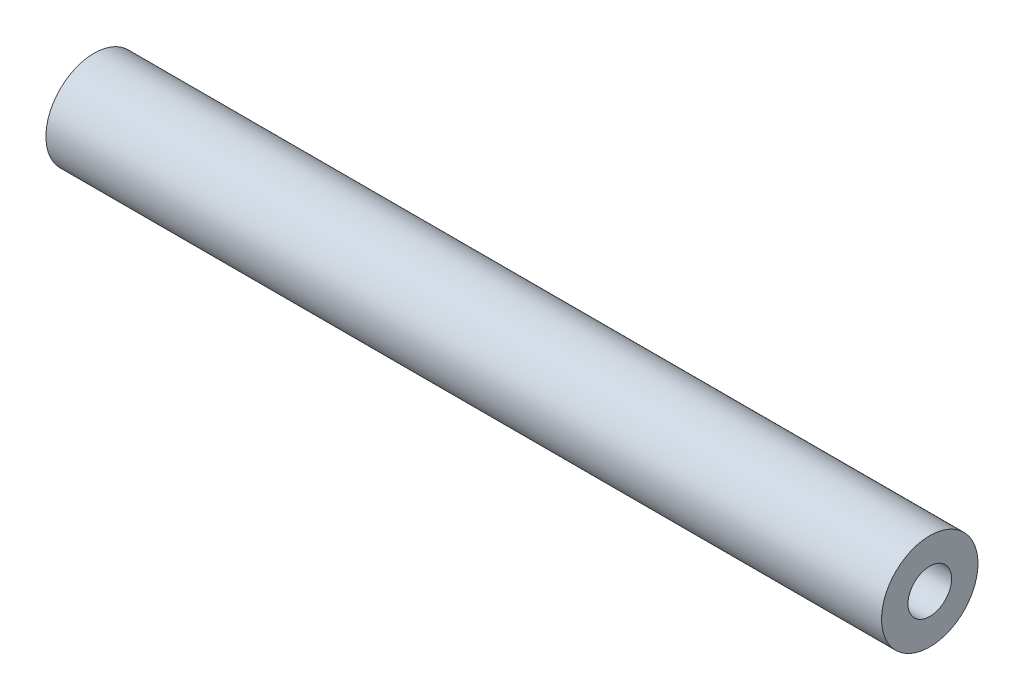
SolidWorks part; units mm, degrees
ref_plane "Front Plane" through (0, 0, 0) normal (0, 0, 1) x (1, 0, 0)
ref_plane "Top Plane" through (0, 0, 0) normal (0, 1, 0) x (1, 0, 0)
ref_plane "Right Plane" through (0, 0, 0) normal (1, 0, 0) x (0, 0, -1)
sketch "Sketch1" plane through (0, 0, 0) normal (1, 0, 0) x (0, 0, -1)
  circle A0 centre (0, 0) radius 4.7625
  circle A1 centre (0, 0) radius 2.1526
  dimension "D1" = 9.525
  dimension "D2" = 4.3053
extrude "Boss-Extrude1" add sketch "Sketch1" along normal blind 82.55
